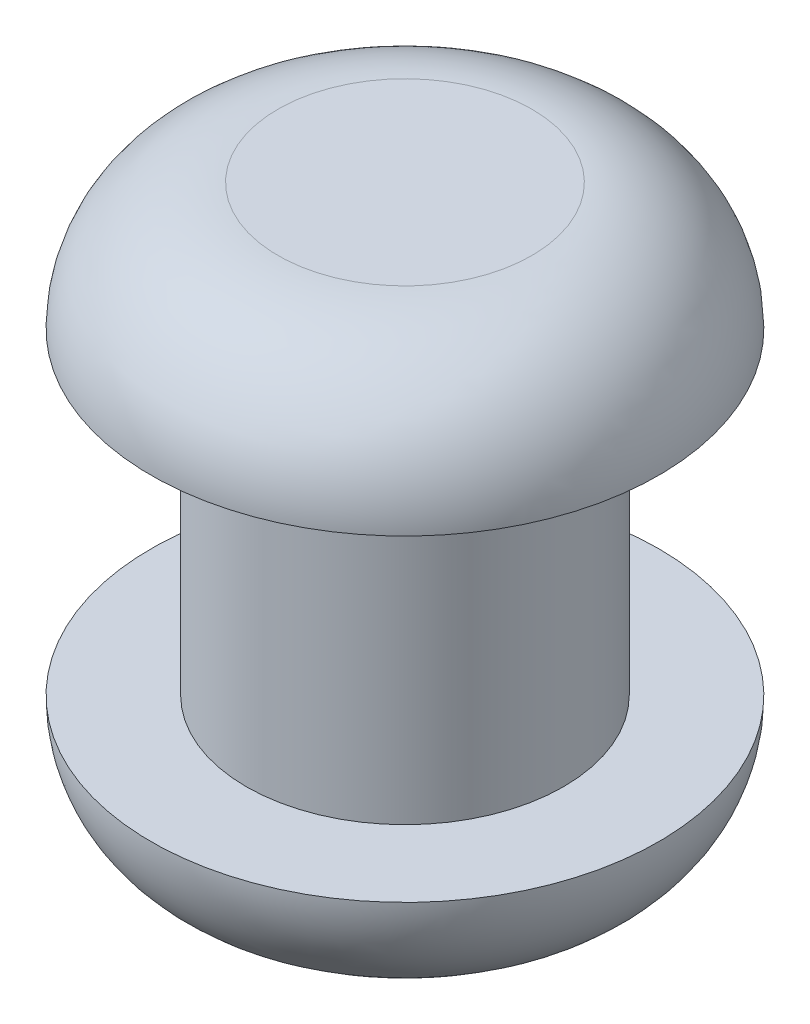
SolidWorks part; units mm, degrees
material "AISI 1045 Steel, cold drawn"
ref_plane "Front Plane" through (0, 0, 0) normal (1, 0, 0) x (0, 1, 0)
ref_plane "Top Plane" through (0, 0, 0) normal (0, 0, 1) x (0, 1, 0)
ref_plane "Right Plane" through (0, 0, 0) normal (0, 1, 0) x (-1, 0, 0)
sketch "Sketch2" plane through (0, 0, 0) normal (1, 0, 0) x (0, 1, 0)
  line L0 (-8.5466, 0) -> (8.2271, 0) construction
  line L1 (0, 5.8686) -> (0, -5.0584) construction
  line L2 (-2.5, 2.5) -> (2.5, 2.5)
  line L3 (2.5, 2.5) -> (2.5, 4)
  line L4 (2.5, 4) -> (4.5, 4) construction
  line L5 (4.5, 2) -> (4.5, 0)
  line L6 (4.5, 4) -> (4.5, 2) construction
  line L7 (-4.5, 2) -> (-4.5, 0)
  line L8 (-2.5, 2.5) -> (-2.5, 4)
  line L9 (-4.5, 0) -> (4.5, 0)
  arc A0 (2.5, 4) -> (4.5, 2) centre (2.5, 2) cw
  arc A1 (-2.5, 4) -> (-4.5, 2) centre (-2.5, 2) ccw
  point P17 (0, 2.5)
  dimension "D3" = 2.5
  dimension "D1" = 5
  dimension "D2" = 8
  dimension "D4" = 2
revolve "Revolve1" add sketch "Sketch2" angle 360 about L0
